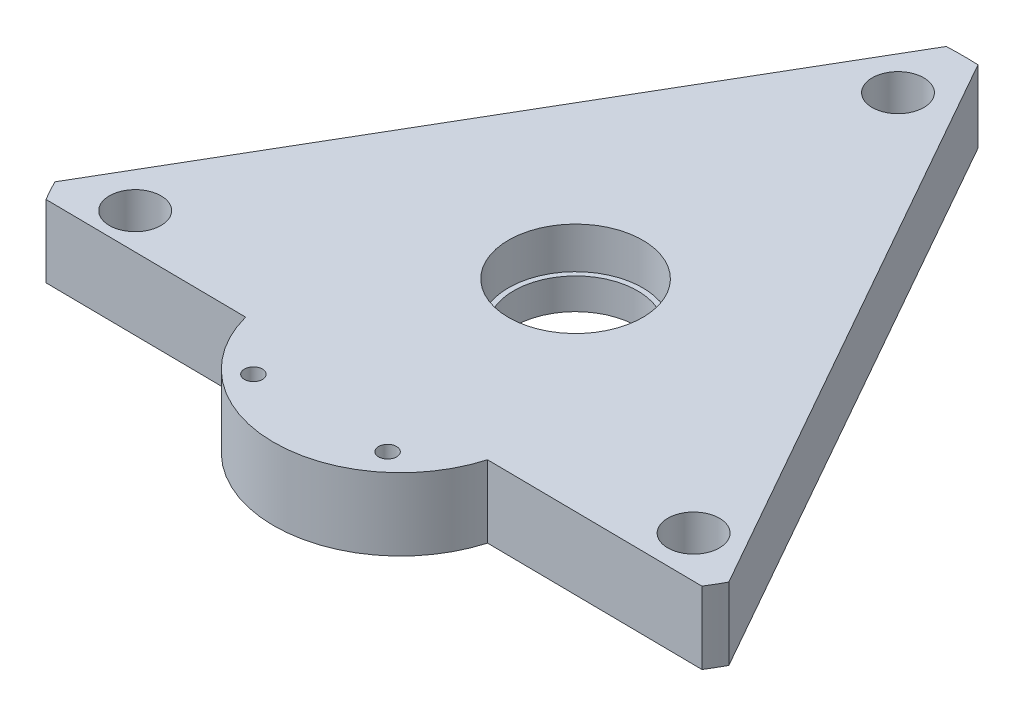
SolidWorks part; units mm, degrees
ref_plane "Front Plane" through (0, 0, 0) normal (0, 0, 1) x (1, 0, 0)
ref_plane "Top Plane" through (0, 0, 0) normal (0, 1, 0) x (1, 0, 0)
ref_plane "Right Plane" through (0, 0, 0) normal (1, 0, 0) x (0, 0, -1)
sketch "Sketch1" plane through (0, 0, 0) normal (0, 1, 0) x (1, 0, 0)
  circle A0 centre (0, 0) radius 75
  dimension "D1" = 150
extrude "Boss-Extrude1" add sketch "Sketch1" along normal blind 14
sketch "Sketch2" plane through (0, 14, 0) normal (0, 1, 0) x (1, 0, 0)
  circle A0 centre (0, 0) radius 13
  dimension "D1" = 26
extrude "Cut-Extrude1" cut sketch "Sketch2" against normal blind 8
sketch "Sketch3" plane through (0, 6, 0) normal (0, 1, 0) x (1, 0, 0)
  circle A0 centre (0, 0) radius 12
  dimension "D1" = 24
extrude "Cut-Extrude2" cut sketch "Sketch3" against normal blind 8
sketch "Sketch4" plane through (0, 14, 0) normal (0, 1, 0) x (1, 0, 0)
  line L0 (0, 0) -> (0, 62.5) construction
  line L1 (0, 0) -> (54.1266, -31.25) construction
  line L2 (0, 0) -> (-54.1266, -31.25) construction
  circle A0 centre (0, 62.5) radius 5
  circle A1 centre (-54.1266, -31.25) radius 5
  circle A2 centre (54.1266, -31.25) radius 5
  circle A3 centre (0, 0) radius 62.5
  dimension "D1" = 10
  dimension "D2" = 10
  dimension "D3" = 10
  dimension "D4" = 62.5
  dimension "D5" = 120
extrude "Cut-Extrude4" cut sketch "Sketch4" against normal through all contours A3 A0 | A0 A3 | A2 A3 | A3 A2 | A3 A1 | A1 A3
cosmetic thread "Cosmetic Thread3" parameters "D2"=11
cosmetic thread "Cosmetic Thread4" parameters "D2"=11
cosmetic thread "Cosmetic Thread5" parameters "D2"=11
sketch "Sketch5" plane through (0, 14, 0) normal (0, 1, 0) x (1, 0, 0)
  line L0 (-33.2016, -67.2507) -> (-33.2016, -57.2507)
  line L1 (-33.2016, -57.2507) -> (28.7984, -57.2507)
  line L2 (-33.2016, -57.2507) -> (-33.2016, -22.2507)
  line L3 (-33.2016, -22.2507) -> (28.7984, -22.2507)
  line L4 (28.7984, -57.2507) -> (28.7984, -22.2507)
  line L5 (28.7984, -57.2507) -> (28.7984, -69.2507)
  circle A0 centre (0, 0) radius 75 construction
  circle A1 centre (-15.2016, -47.2507) radius 1.75
  circle A2 centre (10.7984, -47.2507) radius 1.75
  dimension "D9" = 3.5
  dimension "D10" = 3.5
  dimension "D1" = 35
  dimension "D2" = 62
  dimension "D3" = 10
  dimension "D4" = 12
  dimension "D5" = 10
  dimension "D6" = 10
  dimension "D7" = 18
  dimension "D8" = 18
extrude "Cut-Extrude5" cut sketch "Sketch5" against normal through all contours A1 | A2
cosmetic thread "Cosmetic Thread1" parameters "D2"=4
cosmetic thread "Cosmetic Thread2" parameters "D2"=4
sketch "Sketch6" plane through (0, 0, 0) normal (0, -1, 0) x (-1, 0, 0)
  line L0 (3.073, 74.937) -> (66.7511, -34.1949)
  line L1 (64.6552, -38.0092) -> (-63.8469, -39.352)
  line L2 (-3.073, 74.937) -> (-65.7628, -36.059)
  circle A0 centre (0, 0) radius 75
  circle A1 centre (0, 0) radius 75 construction
  arc A2 (-21.8445, -38.9131) -> (25.5469, -38.4179) centre (1.7831, -32.1469) ccw
  circle M8 centre (0, 0) radius 75
extrude "Cut-Extrude6" cut sketch "Sketch6" against normal blind 15 contours L0 M8 | L2 M8 | A2 L1 M8
